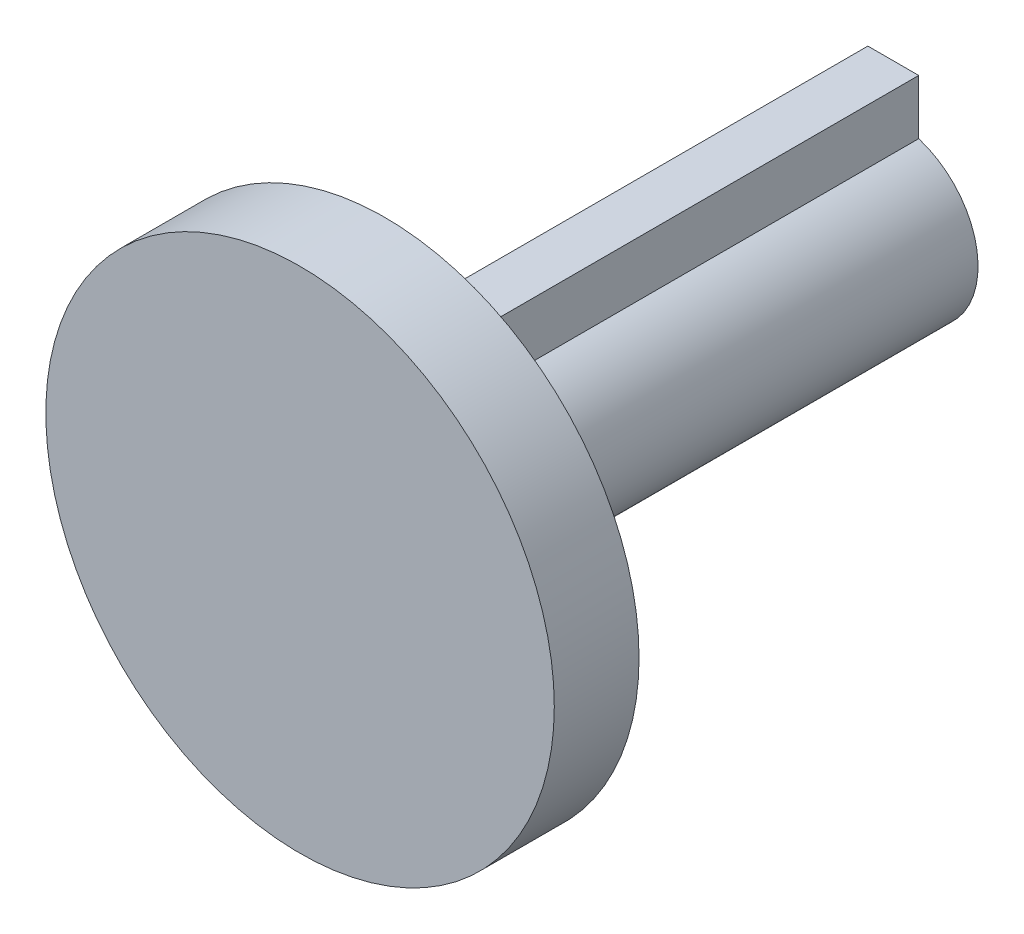
SolidWorks part; units mm, degrees
ref_plane "前视基准面" through (0, 0, 0) normal (0, 0, 1) x (1, 0, 0)
ref_plane "上视基准面" through (0, 0, 0) normal (0, 1, 0) x (1, 0, 0)
ref_plane "右视基准面" through (0, 0, 0) normal (1, 0, 0) x (0, 0, -1)
other "Configuration Table"
sketch "草图1" plane through (0, 0, 0) normal (0, 0, 1) x (1, 0, 0)
  line L0 (0, 0) -> (-1.5, 0)
  line L1 (-1.5, 0) -> (-1.5, 8)
  line L2 (-1.5, 8) -> (1.5, 8)
  line L3 (1.5, 8) -> (1.5, 0)
  line L4 (1.5, 0) -> (0, 0)
  circle A0 centre (0, 0) radius 5
extrude "凸台-拉伸1" add sketch "草图1" along normal blind 30 contours A0 L3 L2 L1 | L3 A0 L1 L0 L4 | L1 A0 L3 L4 L0
sketch "草图2" plane through (0, 0, 30) normal (0, 0, 1) x (1, 0, 0)
  circle A0 centre (0, 0) radius 15
extrude "凸台-拉伸2" add sketch "草图2" along normal blind 5
